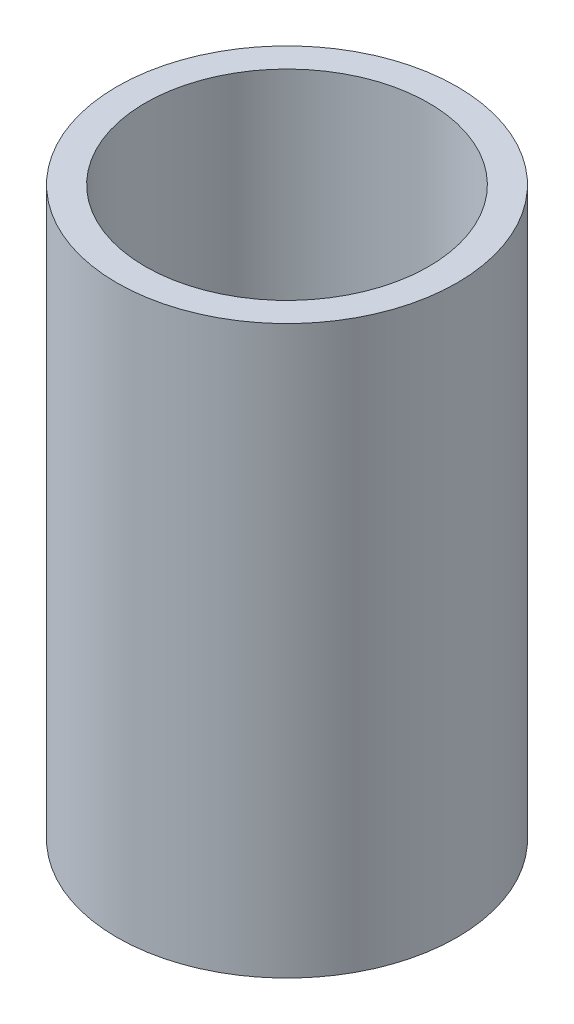
SolidWorks part; units mm, degrees
ref_plane "Front Plane" through (0, 0, 0) normal (0, 0, 1) x (1, 0, 0)
ref_plane "Top Plane" through (0, 0, 0) normal (0, 1, 0) x (1, 0, 0)
ref_plane "Right Plane" through (0, 0, 0) normal (1, 0, 0) x (0, 0, -1)
sketch "Sketch1" plane through (0, 0, 0) normal (0, 1, 0) x (1, 0, 0)
  circle A0 centre (0, 0) radius 12.5
  circle A1 centre (0, 0) radius 15
  dimension "D1" = 25
  dimension "D2" = 30
extrude "Boss-Extrude1" add sketch "Sketch1" along normal blind 50
